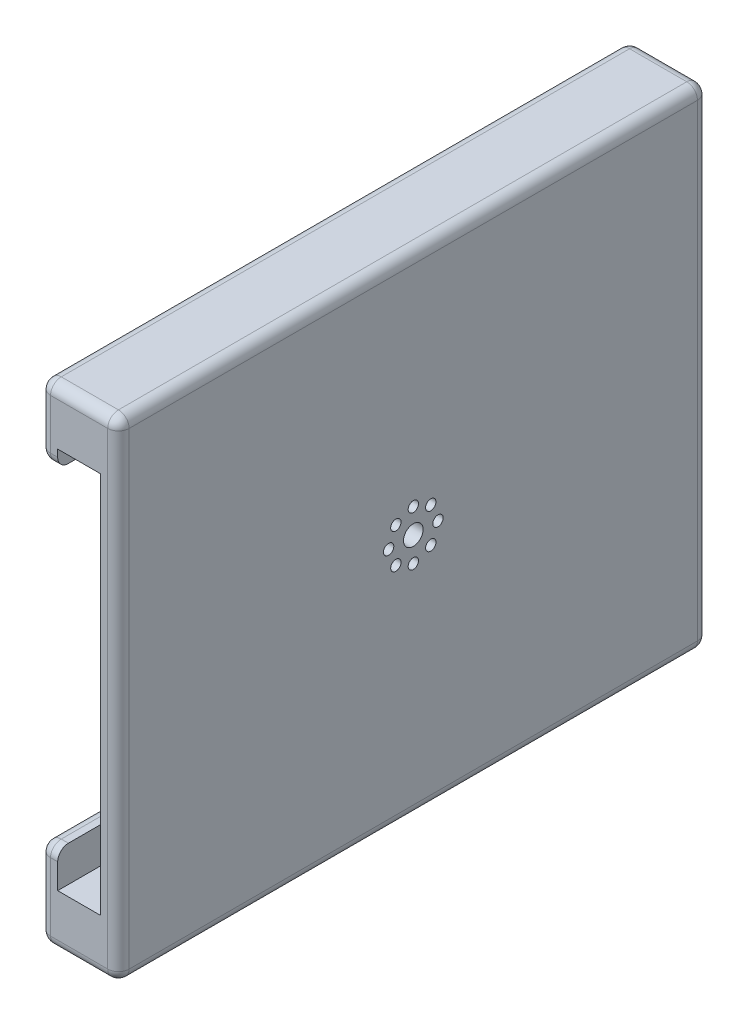
SolidWorks part; units mm, degrees
ref_plane "Front Plane" through (0, 0, 0) normal (0, 0, 1) x (1, 0, 0)
ref_plane "Top Plane" through (0, 0, 0) normal (0, 1, 0) x (1, 0, 0)
ref_plane "Right Plane" through (0, 0, 0) normal (1, 0, 0) x (0, 0, -1)
sketch "Sketch1" plane through (0, 0, 0) normal (1, 0, 0) x (0, 0, -1)
  line L1 (-82.5, 68.5) -> (82.5, 68.5)
  line L2 (-82.5, 68.5) -> (-82.5, -68.5)
  line L3 (-82.5, -68.5) -> (82.5, -68.5)
  line L4 (82.5, 68.5) -> (82.5, -68.5)
  line L5 (-82.5, 68.5) -> (82.5, -68.5) construction
  line L6 (-82.5, -68.5) -> (82.5, 68.5) construction
  point P0 (0, 0)
  dimension "D1" = 165
  dimension "D2" = 137
extrude "Boss-Extrude1" add sketch "Sketch1" along normal blind 22
sketch "Sketch2" plane through (0, 0, 82.5) normal (0, 0, 1) x (1, 0, 0)
  line L0 (0, 68.5) -> (0, -68.5) construction
  line L1 (0, 48.5) -> (5, 48.5)
  line L2 (5, 48.5) -> (5, 53.5)
  line L3 (5, 53.5) -> (17, 53.5)
  line L4 (17, 53.5) -> (17, -53.5)
  line L5 (17, -53.5) -> (5, -53.5)
  line L6 (5, -53.5) -> (5, -43.5)
  line L7 (5, -43.5) -> (0, -43.5)
  line L8 (22, 68.5) -> (22, -68.5) construction
  line L9 (0, 48.5) -> (0, -43.5)
  point P0 (0, 48.5)
  point P1 (0, -43.5)
  dimension "D1" = 25
  dimension "D2" = 20
  dimension "D3" = 5
  dimension "D4" = 107
  dimension "D5" = 5
  dimension "D6" = 12
  dimension "D7" = 12
extrude "Cut-Extrude1" cut sketch "Sketch2" against normal blind 165
fillet "Fillet1" radius 3 6 edges at (0, -68.5, 0) (22, 68.5, 0) (0, 68.5, 0) (0, 48.5, 0) (0, -43.5, 0) (22, -68.5, 0)
sketch "Sketch3" plane through (17, 0, 0) normal (-1, 0, 0) x (0, 0, 1)
  circle A1 centre (0, -0.0843) radius 2.75
  circle A2 centre (6.905, -0.0843) radius 1.45
  circle A3 centre (4.8826, -4.9668) radius 1.45
  circle A4 centre (0, -6.9893) radius 1.45
  circle A5 centre (-4.8826, -4.9668) radius 1.45
  circle A6 centre (-6.905, -0.0843) radius 1.45
  circle A7 centre (-4.8826, 4.7983) radius 1.45
  circle A8 centre (0, 6.8207) radius 1.45
  circle A9 centre (4.8826, 4.7983) radius 1.45
  point P0 (-0.2298, -0.3685)
  point P20 (0, -0.0843)
  dimension "D1" = 5.5
  dimension "D3" = 2.9
  dimension "D4" = 2.9
  dimension "D5" = 2.9
  dimension "D6" = 2.9
  dimension "D7" = 2.9
  dimension "D8" = 2.9
  dimension "D9" = 2.9
  dimension "D10" = 2.9
  dimension "D2" = 6.905
extrude "Cut-Extrude2" cut sketch "Sketch3" against normal blind 5
fillet "Fillet2" radius 3 13 edges at (4, 48.5, -82.5) (0.8787, 49.3787, -82.5) (4, -43.5, -82.5) (0.8787, -44.3787, -82.5) (0, -56, -82.5) (0.8787, -67.6213, -82.5) (11, -68.5, -82.5) (21.1213, -67.6213, -82.5) (22, 0, -82.5) (21.1213, 67.6213, -82.5) (11, 68.5, -82.5) (0.8787, 67.6213, -82.5) (0, 58.5, -82.5)
fillet "Fillet3" radius 3 13 edges at (4, -43.5, 82.5) (0.8787, -44.3787, 82.5) (4, 48.5, 82.5) (0.8787, 49.3787, 82.5) (0, 58.5, 82.5) (0.8787, 67.6213, 82.5) (11, 68.5, 82.5) (21.1213, 67.6213, 82.5) (22, 0, 82.5) (21.1213, -67.6213, 82.5) (11, -68.5, 82.5) (0.8787, -67.6213, 82.5) (0, -56, 82.5)
